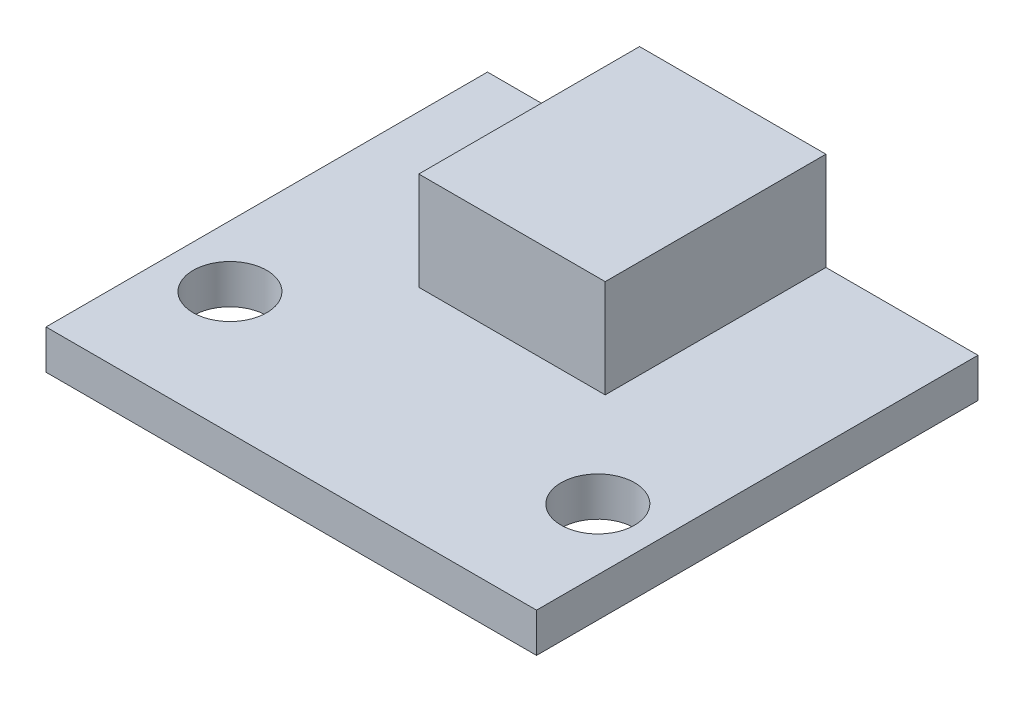
SolidWorks part; units mm, degrees
ref_plane "前视基准面" through (0, 0, 0) normal (0, 0, 1) x (1, 0, 0)
ref_plane "上视基准面" through (0, 0, 0) normal (0, 1, 0) x (1, 0, 0)
ref_plane "右视基准面" through (0, 0, 0) normal (1, 0, 0) x (0, 0, -1)
other "Configuration Table"
sketch "草图1" plane through (0, 0, 0) normal (0, 1, 0) x (1, 0, 0)
  line L0 (10, 18) -> (10, 0) construction
  line L1 (0, 0) -> (20, 0)
  line L2 (0, 0) -> (0, 18)
  line L3 (0, 18) -> (20, 18)
  line L4 (20, 0) -> (20, 18)
  circle A0 centre (2.5, 5) radius 1.5
  circle A1 centre (17.5, 5) radius 1.5
  dimension "D3" = 3
  dimension "D1" = 18
  dimension "D2" = 20
  dimension "D4" = 15
  dimension "D5" = 5
extrude "凸台-拉伸1" add sketch "草图1" along normal blind 1.6
sketch "草图2" plane through (0, 1.6, 0) normal (0, 1, 0) x (1, 0, 0)
  line L0 (10, 18) -> (10, 0) construction
  line L1 (20, 18) -> (0, 18) construction
  line L2 (0, 0) -> (20, 0) construction
  line L4 (6.2, 18) -> (13.8, 18)
  line L5 (6.2, 18) -> (6.2, 9)
  line L6 (6.2, 9) -> (13.8, 9)
  line L7 (13.8, 18) -> (13.8, 9)
  dimension "D1" = 7.6
  dimension "D2" = 9
extrude "凸台-拉伸2" add sketch "草图2" along normal blind 4
